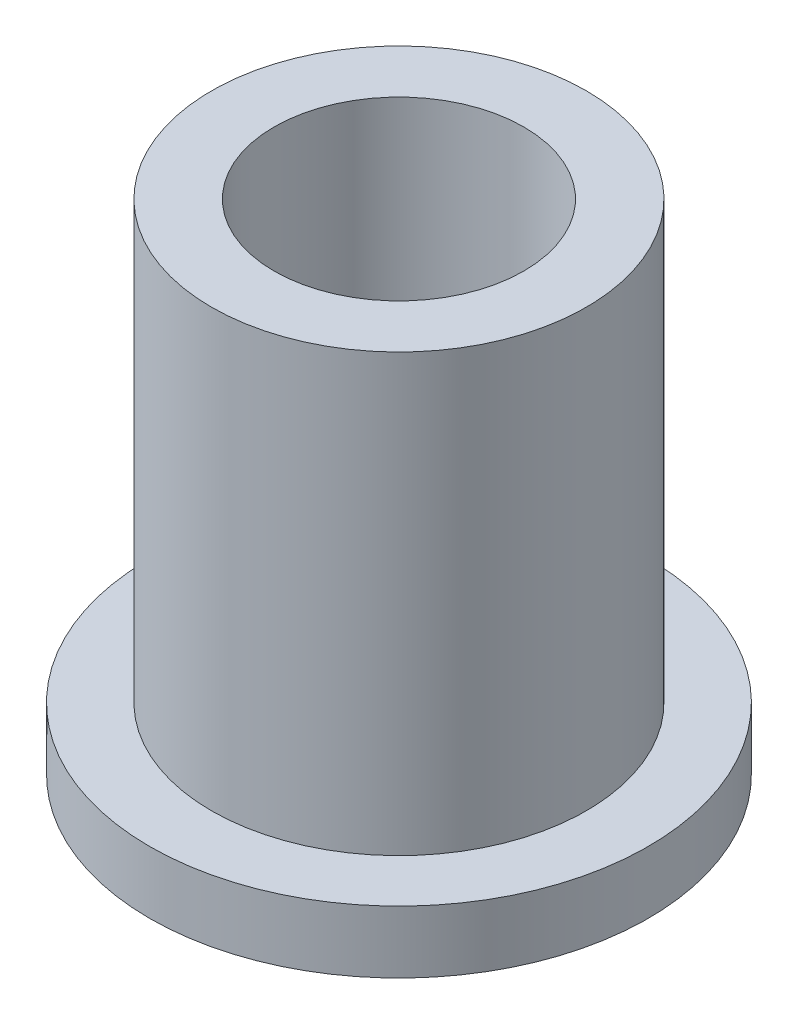
SolidWorks part; units mm, degrees
ref_plane "Front" through (0, 0, 0) normal (0, 0, 1) x (1, 0, 0)
ref_plane "Top" through (0, 0, 0) normal (0, 1, 0) x (1, 0, 0)
ref_plane "Right" through (0, 0, 0) normal (1, 0, 0) x (0, 0, -1)
sketch "Sketch1" plane through (0, 0, 0) normal (0, 1, 0) x (1, 0, 0)
  circle A0 centre (0, 0) radius 6.3627
  circle A1 centre (0, 0) radius 9.5504
  circle A2 centre (0, 0) radius 12.7
  dimension "ID" = 12.7254
  dimension "OD" = 19.1008
  dimension "FlangeOD" = 25.4
sketch "Sketch2" plane through (0, 0, 0) normal (0, 1, 0) x (1, 0, 0)
  circle A0 centre (0, 0) radius 6.3627 construction
  circle A1 centre (0, 0) radius 9.5504 construction
  circle A2 centre (0, 0) radius 6.3627
  circle A3 centre (0, 0) radius 9.5504
extrude "Boss-Extrude1" add sketch "Sketch2" along normal blind 25.4
sketch "Sketch3" plane through (0, 0, 0) normal (0, 1, 0) x (1, 0, 0)
  circle A0 centre (0, 0) radius 12.7 construction
  circle A1 centre (0, 0) radius 9.5504 construction
  circle A2 centre (0, 0) radius 12.7
  circle A3 centre (0, 0) radius 9.5504
extrude "Boss-Extrude2" add sketch "Sketch3" along normal blind 3.175
